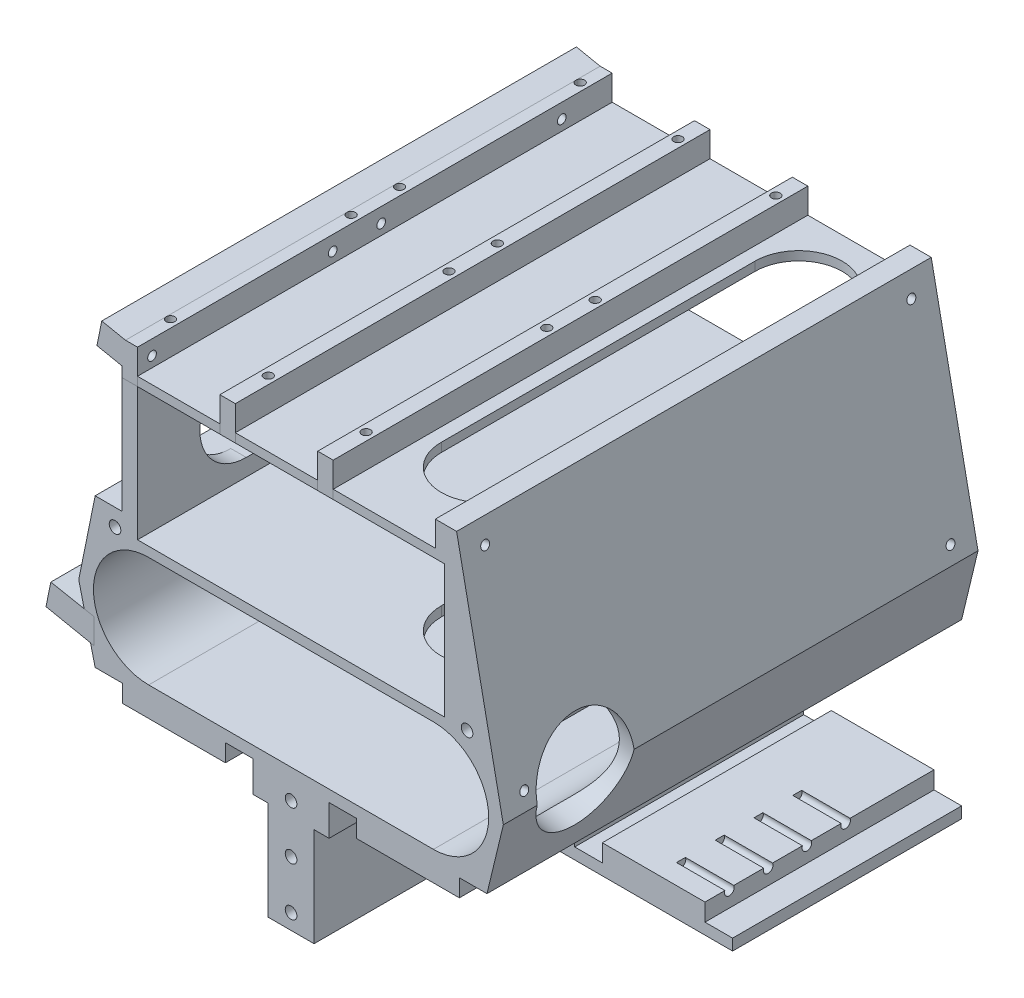
SolidWorks part; units mm, degrees
ref_plane "Plan de face" through (0, 0, 0) normal (0, 0, 1) x (1, 0, 0)
ref_plane "Plan de dessus" through (0, 0, 0) normal (0, 1, 0) x (1, 0, 0)
ref_plane "Plan de droite" through (0, 0, 0) normal (1, 0, 0) x (0, 0, -1)
sketch "Esquisse1" plane through (0, 0, 0) normal (0, 0, 1) x (1, 0, 0)
  line L1 (-56.0863, -46.0305) -> (56.0863, -46.0305)
  line L2 (-56.0863, -46.0305) -> (-56.0863, 46.0305)
  line L3 (-56.0863, 46.0305) -> (56.0863, 46.0305)
  line L4 (56.0863, -46.0305) -> (56.0863, 46.0305)
  line L5 (-56.0863, -46.0305) -> (56.0863, 46.0305) construction
  line L6 (-56.0863, 46.0305) -> (56.0863, -46.0305) construction
  point P0 (0, 0)
extrude "Boss.-Extru.1" add sketch "Esquisse1" along normal blind 98
sketch "Esquisse2" plane through (0, 0, 98) normal (0, 0, 1) x (1, 0, 0)
  line L0 (0, 46.0305) -> (0, -46.0305) construction
  line L1 (56.0863, 46.0305) -> (-56.0863, 46.0305) construction
  line L2 (-56.0863, -46.0305) -> (56.0863, -46.0305) construction
  line L4 (-31.7, 16.7912) -> (31.7, 16.7912)
  line L5 (-31.7, 16.7912) -> (-31.7, 44.1912)
  line L6 (-31.7, 44.1912) -> (31.7, 44.1912)
  line L7 (31.7, 16.7912) -> (31.7, 44.1912)
  line L8 (-31.7, 16.7912) -> (31.7, 44.1912) construction
  line L9 (-31.7, 44.1912) -> (31.7, 16.7912) construction
  point P6 (0, 30.4912)
  dimension "D1" = 63.4
  dimension "D2" = 27.4
extrude "Enlèv. mat.-Extru.1" cut sketch "Esquisse2" against normal through all
sketch "Esquisse3" plane through (0, 0, 98) normal (0, 0, 1) x (1, 0, 0)
  line L0 (-29.4, 3.3912) -> (29.4, 3.3912) construction
  line L1 (-29.4, 14.7912) -> (29.4, 14.7912)
  line L2 (-29.4, -8.0088) -> (29.4, -8.0088)
  line L3 (-31.7, 16.7912) -> (31.7, 16.7912) construction
  line L4 (0, 46.0305) -> (0, -46.0305) construction
  line L5 (56.0863, 46.0305) -> (-56.0863, 46.0305) construction
  line L6 (-56.0863, -46.0305) -> (56.0863, -46.0305) construction
  arc A0 (-29.4, 14.7912) -> (-29.4, -8.0088) centre (-29.4, 3.3912) ccw
  arc A1 (29.4, -8.0088) -> (29.4, 14.7912) centre (29.4, 3.3912) ccw
  point P2 (0, 3.3912)
  dimension "D1" = 2
  dimension "D2" = 0
extrude "Enlèv. mat.-Extru.2" cut sketch "Esquisse3" against normal through all
sketch "Esquisse4" plane through (0, 0, 98) normal (0, 0, 1) x (1, 0, 0)
  line L0 (0, 46.0305) -> (0, -46.0305) construction
  line L1 (56.0863, 46.0305) -> (-56.0863, 46.0305) construction
  line L2 (-56.0863, -46.0305) -> (56.0863, -46.0305) construction
  line L3 (7.95, -40.1088) -> (7.95, -14.0088) construction
  line L4 (13.55, -14.0088) -> (40.35, -14.0088) construction
  line L5 (-29.4, -8.0088) -> (29.4, -8.0088) construction
  line L6 (7.95, -40.1088) -> (40.35, -40.1088) construction
  line L7 (40.35, -14.0088) -> (40.35, -40.1088) construction
  line L8 (-13.55, -10.4088) -> (-13.55, -14.0088)
  line L9 (34.75, -14.0088) -> (13.55, -14.0088) construction
  line L10 (40.45, -10.4088) -> (40.45, -15.4085)
  line L11 (34.75, -40.1088) -> (13.55, -40.1088)
  line L12 (7.85, -10.4088) -> (7.85, -16.8088)
  line L13 (-34.75, -14.0088) -> (-13.55, -14.0088)
  line L14 (-34.75, -10.4088) -> (-34.75, -14.0088)
  line L15 (-40.45, -10.4088) -> (-34.75, -10.4088)
  line L16 (7.85, -37.3088) -> (7.85, -43.7088)
  line L17 (7.85, -10.4088) -> (13.55, -10.4088)
  line L18 (13.55, -10.4088) -> (13.55, -14.0088)
  line L19 (24.15, -14.0088) -> (24.15, -11.6362) construction
  line L20 (40.45, -38.709) -> (40.45, -43.7088)
  line L21 (40.45, -10.4088) -> (34.75, -10.4088)
  line L22 (34.75, -10.4088) -> (34.75, -14.0088)
  line L23 (8, -27.0588) -> (15.6242, -27.0588) construction
  line L24 (-40.45, -10.4088) -> (-40.45, -15.4085)
  line L25 (40.45, -43.7088) -> (34.75, -43.7088)
  line L26 (34.75, -43.7088) -> (34.75, -40.1088)
  line L27 (13.55, -43.7088) -> (13.55, -40.1088)
  line L28 (7.85, -43.7088) -> (13.55, -43.7088)
  line L29 (-40.45, -15.4085) -> (-46.4701, -15.4085)
  line L30 (8, -27.0588) -> (2.2397, -27.0588) construction
  line L31 (40.4, -26.8088) -> (47.9289, -26.8088) construction
  line L32 (7.85, -16.8088) -> (4.75, -16.8088)
  line L33 (4.75, -16.8088) -> (4.75, -37.3088)
  line L34 (40.45, -15.4085) -> (46.4701, -15.4085)
  line L35 (46.4701, -15.4085) -> (46.4701, -38.709)
  line L36 (7.85, -37.3088) -> (4.75, -37.3088)
  line L37 (40.45, -38.709) -> (46.4701, -38.709)
  line L38 (-46.4701, -15.4085) -> (-46.4701, -38.709)
  line L39 (-40.45, -38.709) -> (-46.4701, -38.709)
  line L40 (-40.45, -38.709) -> (-40.45, -43.7088)
  line L41 (-40.45, -43.7088) -> (-34.75, -43.7088)
  line L42 (-34.75, -43.7088) -> (-34.75, -40.1088)
  line L43 (-34.75, -40.1088) -> (-13.55, -40.1088)
  line L44 (-13.55, -43.7088) -> (-13.55, -40.1088)
  line L45 (-7.85, -43.7088) -> (-13.55, -43.7088)
  line L46 (-7.85, -37.3088) -> (-7.85, -43.7088)
  line L47 (-7.85, -37.3088) -> (-4.75, -37.3088)
  line L48 (-4.75, -16.8088) -> (-4.75, -37.3088)
  line L49 (-7.85, -16.8088) -> (-4.75, -16.8088)
  line L50 (-7.85, -10.4088) -> (-7.85, -16.8088)
  line L51 (-7.85, -10.4088) -> (-13.55, -10.4088)
  line L52 (13.55, -14.0088) -> (34.75, -14.0088)
  point P42 (4.75, -27.0588)
  point P45 (46.4701, -27.0588)
  dimension "D1" = 4.75
  dimension "D2" = 6
  dimension "D3" = 32.4
  dimension "D4" = 13.05
  dimension "D5" = 5.7
  dimension "D6" = 6.4
  dimension "D7" = 3.1
  dimension "D8" = 20.5
  dimension "D9" = 10.6
extrude "Enlèv. mat.-Extru.3" cut sketch "Esquisse4" against normal through all
sketch "Esquisse8" plane through (0, 0, 0) normal (0, 0, -1) x (-1, 0, 0)
  line L0 (40.45, -43.7088) -> (40.45, -46.0305) construction
  line L1 (56.0863, -46.0305) -> (-56.0863, -46.0305) construction
  line L2 (40.45, -10.4088) -> (43.8315, 3.5912) construction
  line L3 (43.8315, 3.5912) -> (40.45, 20.287) construction
  line L4 (40.45, 20.287) -> (34.9042, 20.287) construction
  line L5 (34.9042, 20.287) -> (34.9042, 46.0305) construction
  line L6 (-56.0863, 46.0305) -> (56.0863, 46.0305) construction
  line L7 (40.45, -46.0305) -> (40.45, -10.4088)
  line L8 (40.45, -10.4088) -> (43.8315, 3.5912)
  line L9 (43.8315, 3.5912) -> (40.45, 20.287)
  line L10 (40.45, 20.287) -> (34.9042, 20.287)
  line L11 (34.9042, 20.287) -> (34.9042, 46.0305)
  line L12 (0, -46.0305) -> (0, 46.0305) construction
  line L13 (-40.45, -46.0305) -> (-40.45, -10.4088)
  line L14 (-40.45, -10.4088) -> (-43.8315, 3.5912)
  line L15 (-43.8315, 3.5912) -> (-40.45, 20.287)
  line L18 (-35.236, 46.0305) -> (-56.0863, 46.0305)
  line L19 (-56.0863, 46.0305) -> (-56.0863, -46.0305)
  line L20 (-56.0863, -46.0305) -> (-40.45, -46.0305)
  line L21 (40.45, -46.0305) -> (56.0863, -46.0305)
  line L22 (56.0863, -46.0305) -> (56.0863, 46.0305)
  line L23 (56.0863, 46.0305) -> (34.9042, 46.0305)
  line L24 (-40.45, 20.287) -> (-35.236, 46.0305)
  circle A0 centre (36.3424, 16.7291) radius 1.2
  circle A1 centre (-36.3424, 16.7291) radius 1.2
  circle A2 centre (0, -24.0305) radius 1.2
  circle A3 centre (0, -34.0305) radius 1.2
  circle A4 centre (0, -14.0305) radius 1.2
  dimension "D1" = 12
  dimension "D2" = 3
extrude "Enlèv. mat.-Extru.5" cut sketch "Esquisse8" against normal through all
sketch "Esquisse9" plane through (-34.75, 0, 0) normal (-1, 0, 0) x (0, 0, 1)
  circle A0 centre (18.25, -13.5088) radius 1
  circle A1 centre (26.25, -13.5088) radius 1
  circle A2 centre (34.25, -13.5088) radius 1
  circle A3 centre (42.25, -13.5088) radius 1
  circle A4 centre (18.25, -40.5088) radius 1
  circle A5 centre (26.25, -40.5088) radius 1
  circle A6 centre (34.25, -40.5088) radius 1
  circle A7 centre (42.25, -40.5088) radius 1
extrude "Enlèv. mat.-Extru.6" cut sketch "Esquisse9" against normal blind 10
sketch "Esquisse10" plane through (34.75, 0, 0) normal (1, 0, 0) x (0, 0, -1)
  circle A0 centre (-42.25, -13.5088) radius 1
  circle A1 centre (-34.25, -13.5088) radius 1
  circle A2 centre (-26.25, -13.5088) radius 1
  circle A3 centre (-18.25, -13.5088) radius 1
  circle A4 centre (-18.25, -40.5088) radius 1
  circle A5 centre (-26.25, -40.5088) radius 1
  circle A6 centre (-34.25, -40.5088) radius 1
  circle A7 centre (-42.25, -40.5088) radius 1
extrude "Enlèv. mat.-Extru.7" cut sketch "Esquisse10" against normal blind 10
sketch "Esquisse11" plane through (-4.75, 0, 0) normal (-1, 0, 0) x (0, 0, 1)
  line L1 (51.2881, -37.2099) -> (98, -37.2099)
  line L2 (51.2881, -37.2099) -> (51.2881, -52.7634)
  line L3 (51.2881, -52.7634) -> (98, -52.7634)
  line L4 (98, -37.2099) -> (98, -52.7634)
extrude "Enlèv. mat.-Extru.8" cut sketch "Esquisse11" against normal blind 54 and the other way blind 44
sketch "Esquisse12" plane through (0, -37.2099, 0) normal (0, -1, 0) x (1, 0, 0)
  line L0 (0, 98) -> (0, 51.2881) construction
  line L1 (-4.75, 98) -> (4.75, 98) construction
  line L2 (-4.75, 51.2881) -> (4.75, 51.2881) construction
  line L3 (-4.75, 51.2881) -> (4.75, 51.2881) construction
  circle A0 centre (0, 91.9881) radius 1.2
  circle A1 centre (0, 53.2881) radius 1.2
  dimension "D1" = 38.7
  dimension "D2" = 2
extrude "Enlèv. mat.-Extru.9" cut sketch "Esquisse12" against normal blind 15
sketch "Esquisse13" plane through (0, 46.0305, 0) normal (0, 1, 0) x (1, 0, 0)
  line L0 (20.43, -13.6311) -> (20.43, -78.4445) construction
  line L1 (29.4015, -13.6311) -> (29.4015, -78.4445)
  line L2 (11.4585, -13.6311) -> (11.4585, -78.4445)
  arc A0 (29.4015, -13.6311) -> (11.4585, -13.6311) centre (20.43, -13.6311) ccw
  arc A1 (11.4585, -78.4445) -> (29.4015, -78.4445) centre (20.43, -78.4445) ccw
  point P2 (20.43, -46.0378)
extrude "Enlèv. mat.-Extru.10" cut sketch "Esquisse13" against normal blind 36
sketch "Esquisse14" plane through (0, 0, 0) normal (0, 0, -1) x (-1, 0, 0)
  line L0 (-35.236, 46.0305) -> (-34.1813, 51.2377)
  line L1 (-34.1813, 51.2377) -> (-29.7868, 51.2377)
  line L2 (-29.7868, 51.2377) -> (-29.7868, 46.0305)
  line L3 (-35.236, 46.0305) -> (34.9042, 46.0305) construction
  line L4 (-29.7868, 46.0305) -> (-35.236, 46.0305)
extrude "Boss.-Extru.2" add sketch "Esquisse14" against normal through all
sketch "Esquisse15" plane through (42.803, 8.6693, 0) normal (0.9801, 0.1985, 0) x (0, 0, -1)
  circle A0 centre (-5.0126, -1.8311) radius 0.9
  circle A1 centre (-5.0126, 38.8689) radius 0.9
  circle A2 centre (-93.0126, -1.8311) radius 0.9
  circle A3 centre (-93.0126, 38.8689) radius 0.9
extrude "Enlèv. mat.-Extru.11" cut sketch "Esquisse15" against normal blind 5
sketch "Esquisse17" plane through (-34.9042, 0, 0) normal (-1, 0, 0) x (0, 0, 1)
  line L0 (11.8912, 29.8641) -> (75.5405, 29.8641) construction
  line L1 (11.8912, 39.4412) -> (75.5405, 39.4412)
  line L2 (11.8912, 20.287) -> (75.5405, 20.287)
  line L3 (98, 20.287) -> (0, 20.287) construction
  arc A0 (11.8912, 39.4412) -> (11.8912, 20.287) centre (11.8912, 29.8641) ccw
  arc A1 (75.5405, 20.287) -> (75.5405, 39.4412) centre (75.5405, 29.8641) ccw
  point P2 (43.7159, 29.8641)
extrude "Enlèv. mat.-Extru.13" cut sketch "Esquisse17" against normal blind 33
sketch "Esquisse18" plane through (40.5957, -9.8054, 0) normal (0.972, -0.2348, 0) x (0, 0, -1)
  line L0 (-98, 13.7819) -> (0, 13.7819) construction
  line L1 (-98, -0.6207) -> (-98, 13.7819) construction
  circle A0 centre (-81, 13.7819) radius 10
  dimension "D1" = 17
extrude "Enlèv. mat.-Extru.14" cut sketch "Esquisse18" against normal blind 7
sketch "Esquisse19" plane through (0, 0, 0) normal (0, 0, -1) x (-1, 0, 0)
  line L0 (34.9042, 46.0305) -> (34.9042, 20.287) construction
  line L1 (31.7, 44.1912) -> (34.9042, 44.1912)
  line L2 (31.7, 44.1912) -> (31.7, 51.2377)
  line L3 (31.7, 51.2377) -> (34.9042, 51.2377)
  line L4 (34.9042, 44.1912) -> (34.9042, 51.2377)
  line L5 (-29.7868, 51.2377) -> (40.1618, 51.2377) construction
  line L6 (-31.7, 44.1912) -> (31.7, 44.1912) construction
  line L7 (14.7, 44.1912) -> (11.5, 44.1912)
  line L8 (14.7, 44.1912) -> (14.7, 51.2377)
  line L9 (14.7, 51.2377) -> (11.5, 51.2377)
  line L10 (11.5, 44.1912) -> (11.5, 51.2377)
  line L12 (-5.5, 44.1912) -> (-8.7, 44.1912)
  line L13 (-5.5, 44.1912) -> (-5.5, 51.2377)
  line L14 (-5.5, 51.2377) -> (-8.7, 51.2377)
  line L15 (-8.7, 44.1912) -> (-8.7, 51.2377)
  dimension "D1" = 3.2
  dimension "D2" = 17
  dimension "D3" = 3.2
  dimension "D4" = 17
extrude "Boss.-Extru.3" add sketch "Esquisse19" against normal through all
sketch "Esquisse20" plane through (0, 51.2377, 0) normal (0, 1, 0) x (1, 0, 0)
  line L0 (-33.3021, 0) -> (-33.3021, -98.0001) construction
  line L1 (-34.9042, 0) -> (-31.7, 0) construction
  line L2 (-34.9042, -98.0001) -> (-31.7, -98.0001) construction
  line L3 (-23.2, 0) -> (-23.2, -98) construction
  line L4 (-14.7, 0) -> (-31.7, 0) construction
  line L5 (-14.7, -98) -> (-31.7, -98) construction
  line L6 (-3, 0) -> (-3, -98) construction
  line L7 (5.5, 0) -> (-11.5, 0) construction
  line L8 (5.5, -98) -> (-11.5, -98) construction
  line L9 (-13.1, 0) -> (-13.1, -98.0001) construction
  line L10 (-14.7, 0) -> (-11.5, 0) construction
  line L11 (-14.7, -98.0001) -> (-11.5, -98.0001) construction
  circle A0 centre (-33.3021, -5) radius 0.9
  circle A1 centre (-33.3021, -42.3) radius 0.9
  circle A2 centre (-33.3021, -52.3) radius 0.9
  circle A3 centre (-33.3021, -89.6) radius 0.9
  circle A4 centre (-13.1021, -42.3) radius 0.9
  circle A5 centre (-13.1021, -52.3) radius 0.9
  circle A6 centre (-13.1021, -89.6) radius 0.9
  circle A7 centre (-13.1021, -5) radius 0.9
  circle A8 centre (7.0979, -42.3) radius 0.9
  circle A9 centre (7.0979, -52.3) radius 0.9
  circle A10 centre (7.0979, -89.6) radius 0.9
  circle A11 centre (7.0979, -5) radius 0.9
  dimension "D1" = 5
  dimension "D2" = 37.3
  dimension "D3" = 10
  dimension "D4" = 37.3
  dimension "D5" = 3
extrude "Enlèv. mat.-Extru.15" cut sketch "Esquisse20" against normal blind 8
sketch "Esquisse21" plane through (0, 0, 0) normal (0, 0, -1) x (-1, 0, 0)
  line L0 (41.7319, 13.9577) -> (32.7666, 58.2228) construction
  line L1 (40.45, 20.287) -> (43.8315, 3.5912) construction
  line L2 (34.1813, 51.2377) -> (39.0818, 52.2302) construction
  line L3 (34.9042, 51.2377) -> (31.7, 51.2377) construction
  line L4 (39.0818, 52.2302) -> (40.0743, 47.3297) construction
  line L5 (40.0743, 47.3297) -> (35.1738, 46.3372) construction
  line L6 (44.7022, -0.7076) -> (49.6027, 0.285) construction
  line L7 (49.6027, 0.285) -> (50.5953, -4.6155) construction
  line L8 (50.5953, -4.6155) -> (45.6948, -5.6081) construction
  line L9 (39.5781, 49.78) -> (34.6776, 48.7874) construction
  line L10 (50.099, -2.1653) -> (45.1985, -3.1578) construction
  line L11 (41.7319, 13.9577) -> (45.6948, -5.6081) construction
  line L12 (49.6027, 0.285) -> (40.6878, -1.4371)
  line L13 (49.6027, 0.285) -> (50.5953, -4.6155)
  line L14 (50.5953, -4.6155) -> (40.6878, -6.6222)
  line L15 (40.6878, -6.6222) -> (40.6878, -1.4371)
  line L16 (39.0818, 52.2302) -> (40.0743, 47.3297)
  line L17 (40.0743, 47.3297) -> (34.1813, 46.1362)
  line L18 (34.1813, 46.1362) -> (34.1813, 51.2377)
  line L19 (34.1813, 51.2377) -> (39.0818, 52.2302)
  dimension "D1" = 5
  dimension "D2" = 5
  dimension "D3" = 53
  dimension "D4" = 5
  dimension "D5" = 5
extrude "Boss.-Extru.4" add sketch "Esquisse21" against normal through all
sketch "Esquisse22" plane through (-47.7035, 9.6618, 0) normal (-0.9801, 0.1985, 0) x (0, 0, 1)
  line L0 (98.0001, 40.9328) -> (0, 40.9328) construction
  line L1 (98.0001, 38.4328) -> (98.0001, 43.4328) construction
  line L2 (0, 38.4328) -> (0, 43.4328) construction
  line L3 (98.0001, -12.0672) -> (0, -12.0672) construction
  line L4 (98.0001, -14.5672) -> (98.0001, -9.5672) construction
  line L5 (0, -14.5672) -> (0, -9.5672) construction
  line L6 (95.0001, 40.9328) -> (95.0001, -12.0672) construction
  circle A0 centre (95.0001, 40.9328) radius 0.9
  circle A1 centre (57.7001, 40.9328) radius 0.9
  circle A2 centre (95.0001, -12.0672) radius 0.9
  circle A3 centre (57.7001, -12.0672) radius 0.9
  circle A4 centre (47.7001, 40.9328) radius 0.9
  circle A5 centre (10.4001, 40.9328) radius 0.9
  circle A6 centre (47.7001, -12.0672) radius 0.9
  circle A7 centre (10.4001, -12.0672) radius 0.9
  dimension "D1" = 3
  dimension "D2" = 37.3
  dimension "D3" = 37.3
  dimension "D4" = 10
  dimension "D5" = 37.3
  dimension "D6" = 10
  dimension "D7" = 37.3
extrude "Enlèv. mat.-Extru.16" cut sketch "Esquisse22" against normal blind 9
sketch "Esquisse23" plane through (0, -46.0305, 0) normal (0, -1, 0) x (1, 0, 0)
  line L0 (0, 51.2881) -> (0, 47.2881) construction
  line L1 (-40.45, 51.2881) -> (40.45, 51.2881) construction
  line L2 (-43.0065, 51.2881) -> (-43.0065, 47.2881) construction
  line L4 (-43.0065, 47.2881) -> (42.3043, 47.2881) construction
  line L5 (42.3043, 47.2881) -> (42.3043, 51.2881) construction
  line L6 (42.3043, 51.2881) -> (-43.0065, 51.2881) construction
  line L8 (-43.0065, 51.2881) -> (42.3043, 51.2881)
  line L9 (-43.0065, 51.2881) -> (-43.0065, 47.2881)
  line L10 (-43.0065, 47.2881) -> (42.3043, 47.2881)
  line L11 (42.3043, 51.2881) -> (42.3043, 47.2881)
  dimension "D1" = 4
extrude "Enlèv. mat.-Extru.17" cut sketch "Esquisse23" against normal up to surface (8.8207 mm away) up to face at (1.2, -37.2099, 53.2881)
